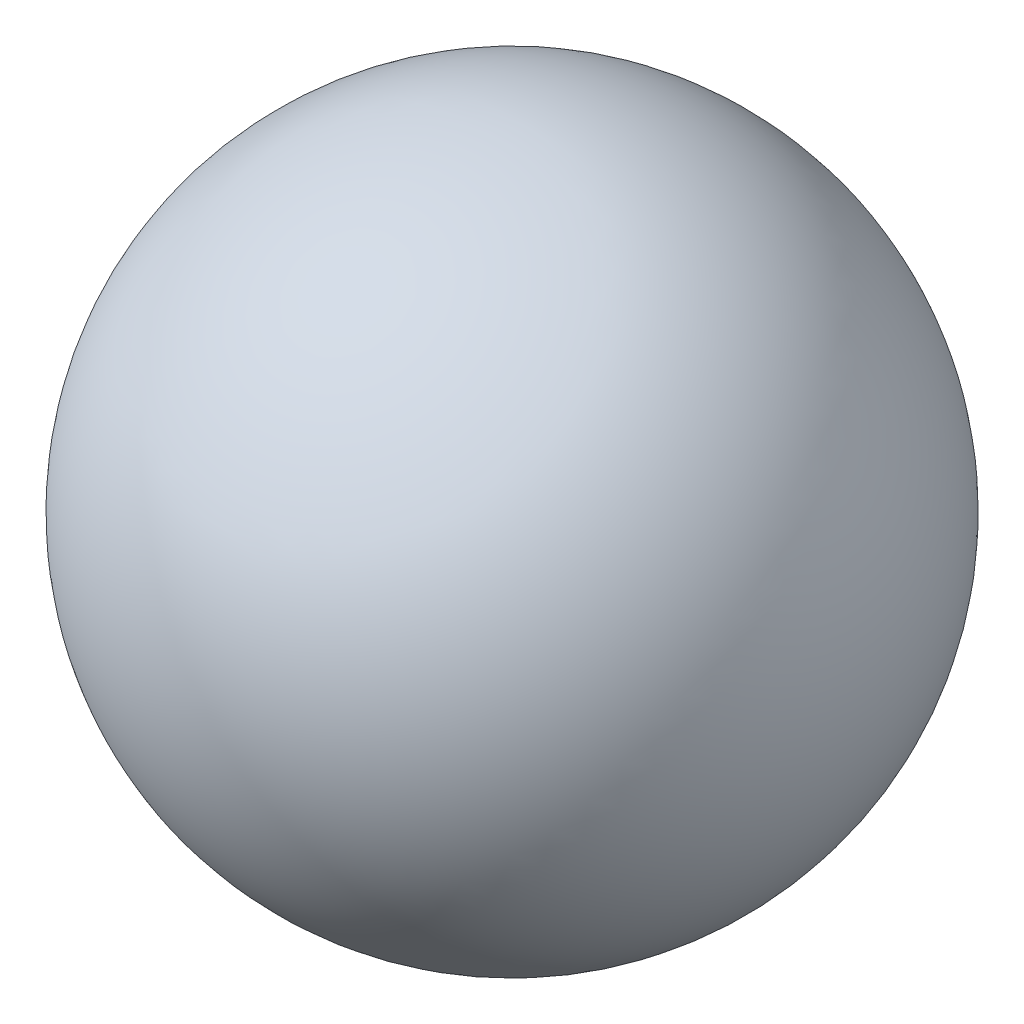
SolidWorks part; units mm, degrees
material "AISI 304"
ref_plane "Front Plane" through (0, 0, 0) normal (0, 0, 1) x (1, 0, 0)
ref_plane "Top Plane" through (0, 0, 0) normal (0, 1, 0) x (1, 0, 0)
ref_plane "Right Plane" through (0, 0, 0) normal (1, 0, 0) x (0, 0, -1)
sketch "Sketch1" plane through (0, 0, 0) normal (0, 1, 0) x (1, 0, 0)
  line L1 (0, -13.4937) -> (0, 13.4937)
  arc A1 (0, -13.4937) -> (0, 13.4937) centre (0, 0) ccw
  point P7 (0, 0)
  dimension "D1" = 26.9875
revolve "Revolve1" add sketch "Sketch1" angle 360 about L1
